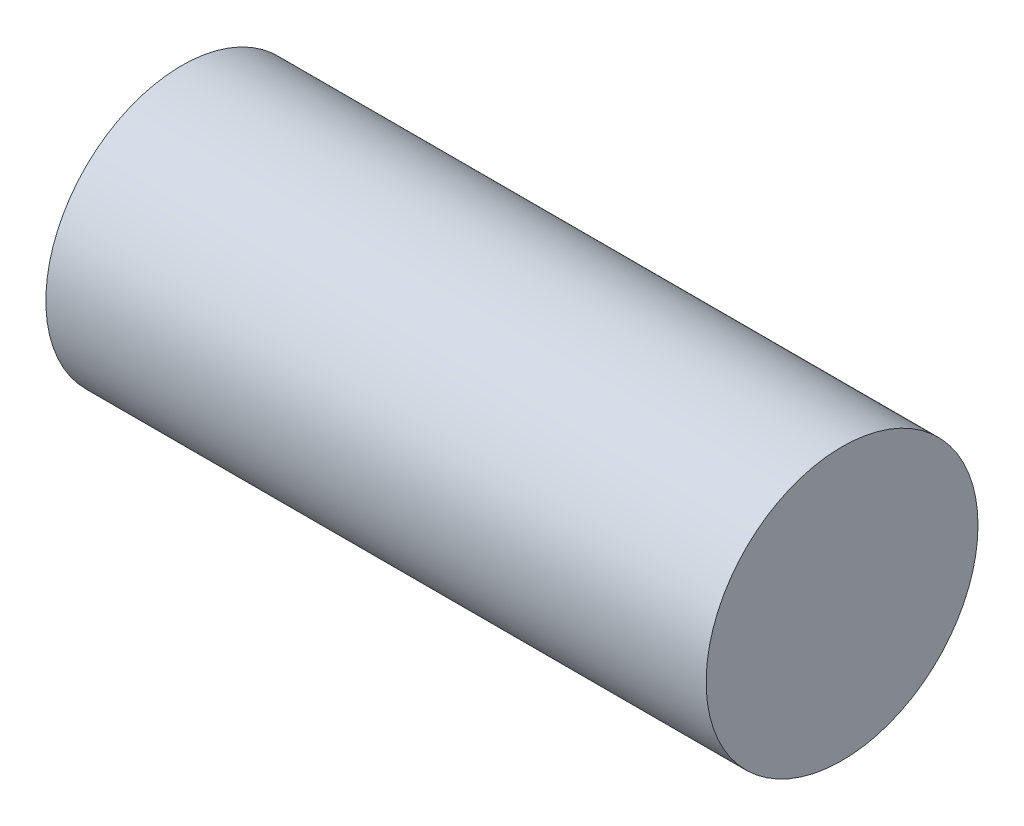
SolidWorks part; units mm, degrees
ref_plane "Front Plane" through (0, 0, 0) normal (0, 0, 1) x (1, 0, 0)
ref_plane "Top Plane" through (0, 0, 0) normal (0, 1, 0) x (1, 0, 0)
ref_plane "Right Plane" through (0, 0, 0) normal (1, 0, 0) x (0, 0, -1)
sketch "Sketch1" plane through (0, 0, 0) normal (1, 0, 0) x (0, 0, -1)
  circle A0 centre (0, 0) radius 1.75
  dimension "D1" = 3.5
extrude "Boss-Extrude1" add sketch "Sketch1" along normal mid plane 8.5
